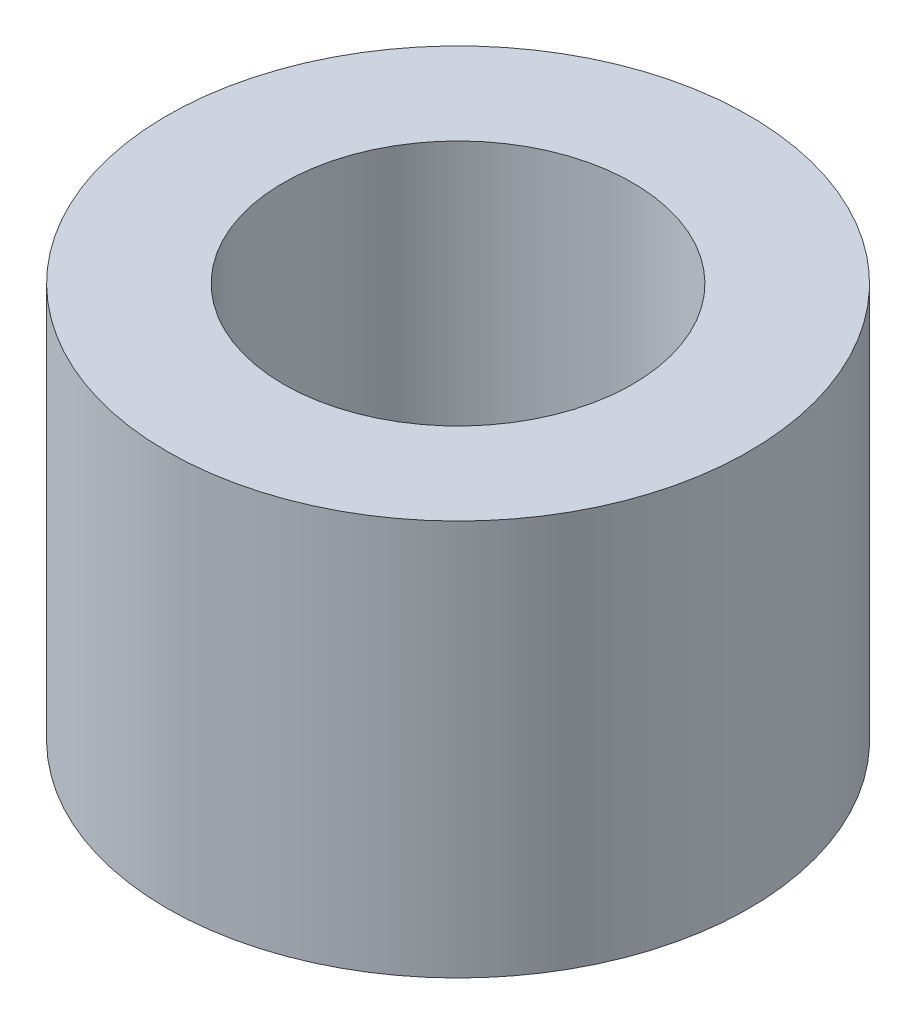
SolidWorks part; units mm, degrees
ref_plane "前视基准面" through (0, 0, 0) normal (0, 0, 1) x (1, 0, 0)
ref_plane "上视基准面" through (0, 0, 0) normal (0, 1, 0) x (1, 0, 0)
ref_plane "右视基准面" through (0, 0, 0) normal (1, 0, 0) x (0, 0, -1)
other "Configuration Table"
sketch "草图1" plane through (0, 0, 0) normal (0, 1, 0) x (1, 0, 0)
  circle A0 centre (0, 0) radius 2.5
  circle A1 centre (0, 0) radius 1.5
  dimension "D1" = 3
  dimension "D2" = 5
extrude "凸台-拉伸1" add sketch "草图1" along normal blind 3.4
